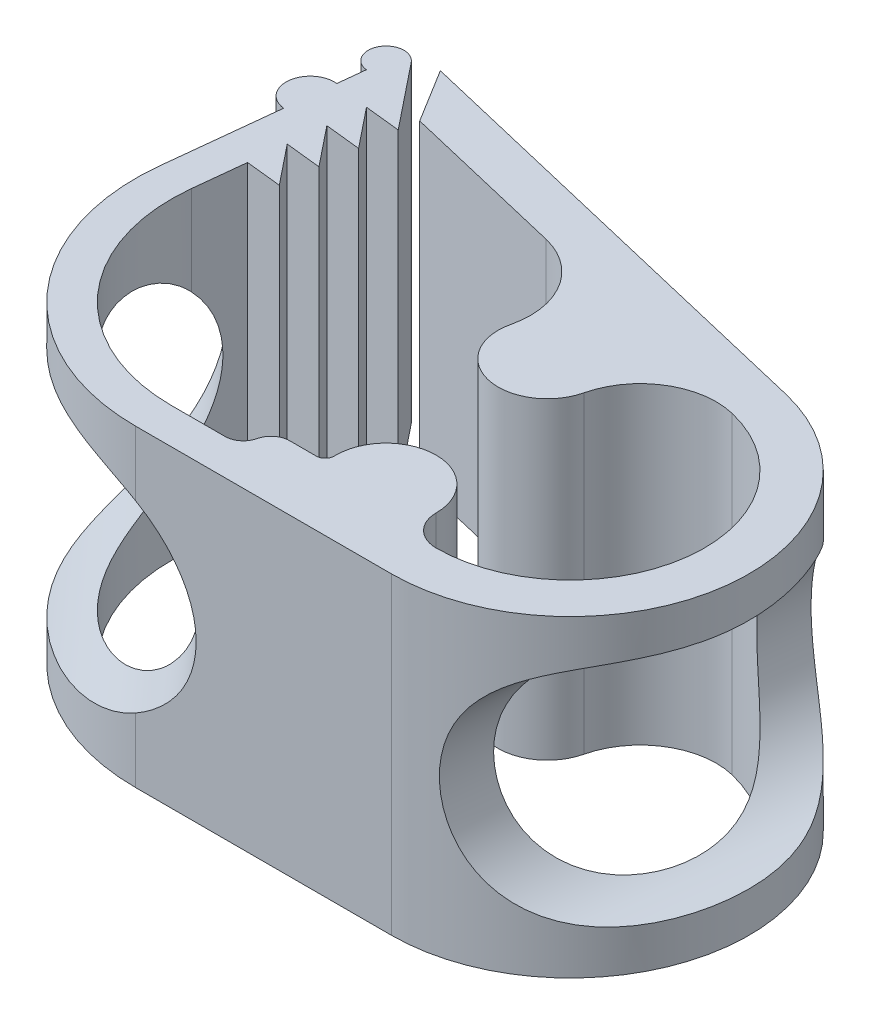
SolidWorks part; units mm, degrees
ref_plane "Front Plane" through (0, 0, 0) normal (0, 0, 1) x (1, 0, 0)
ref_plane "Top Plane" through (0, 0, 0) normal (0, 1, 0) x (1, 0, 0)
ref_plane "Right Plane" through (0, 0, 0) normal (1, 0, 0) x (0, 0, -1)
sketch "Sketch1" plane through (0, 0, 0) normal (0, 1, 0) x (1, 0, 0)
  line L0 (14.3, -12) -> (0, -12)
  line L1 (-11.9306, 1.2885) -> (-11.2565, 7.5301)
  line L2 (-10.9666, 10.2145) -> (-10.8056, 11.7058)
  line L3 (-9.9174, 13.3248) -> (-7.001, 9.6806)
  line L4 (-7.001, 9.6806) -> (-8.9895, 9.8954)
  line L5 (-8.9895, 9.8954) -> (-7.217, 7.6806)
  line L6 (-7.217, 7.6806) -> (-9.2055, 7.8954)
  line L7 (-9.2055, 7.8954) -> (-7.433, 5.6806)
  line L8 (-7.433, 5.6806) -> (-9.4215, 5.8954)
  line L13 (-9.4215, 5.8954) -> (-7.649, 3.6806)
  line L14 (-7.649, 3.6806) -> (-9.6375, 3.8954)
  line L15 (-9.6375, 3.8954) -> (-9.9422, 1.0737)
  line L16 (0, -10) -> (3, -10)
  line L17 (5, -8.4) -> (6.5, -8.4)
  line L18 (7, -7.9) -> (7, -7.8)
  line L19 (2.4072, 8.5266) -> (-6.8367, 10.7176)
  line L21 (-6.8367, 10.7176) -> (-8.6928, 13.7268)
  line L22 (-8.6928, 13.7268) -> (16.6063, 7.7304)
  line L23 (3, -10) -> (5, -8.4) construction
  line L24 (14.3, -2) -> (14.3, -12) construction
  line L25 (14.3, -2) -> (16.6063, 7.7304) construction
  line L26 (5.5624, 3.411) -> (10.9141, 2.1426) construction
  line L27 (-25.5754, -10.6267) -> (-9.9942, 15.87) construction
  line L28 (10.7621, -27.7443) -> (29.0086, 3.2849) construction
  line L29 (-11.5602, 13.2069) -> (22.9201, -7.069) construction
  line L30 (-8.4592, 11.5027) -> (-7.7647, 12.2222) construction
  arc A0 (0, -12) -> (-11.9306, 1.2885) centre (0, 0) cw
  arc A1 (-11.2565, 7.5301) -> (-10.9666, 10.2145) centre (-11.1116, 8.8723) cw
  arc A2 (-10.8056, 11.7058) -> (-9.9174, 13.3248) centre (-10.6982, 12.7) cw
  arc A3 (-9.9422, 1.0737) -> (0, -10) centre (0, 0) ccw
  arc A4 (3, -10) -> (4, -9.2) centre (3, -8.975) ccw
  arc A5 (4, -9.2) -> (5, -8.4) centre (5, -9.425) cw
  arc A6 (6.5, -8.4) -> (7, -7.9) centre (6.5, -7.9) ccw
  arc A7 (7, -7.8) -> (12.6, -7.8) centre (9.8, -7.8) cw
  arc A8 (12.6, -7.8) -> (14.3, -9.5) centre (14.3, -7.8) ccw
  arc A9 (14.3, -9.5) -> (16.0297, 5.2978) centre (14.3, -2) ccw
  arc A10 (16.0297, 5.2978) -> (10.9141, 2.1426) centre (15.0496, 1.1624) ccw
  arc A11 (10.9141, 2.1426) -> (5.5624, 3.411) centre (8.2383, 2.7768) cw
  arc A12 (5.5624, 3.411) -> (2.4072, 8.5266) centre (1.427, 4.3912) ccw
  arc A14 (16.6063, 7.7304) -> (14.3, -12) centre (14.3, -2) cw
  point P16 (0, 0)
  point P17 (0, 0)
  point P18 (0, 0)
  point P19 (-6.226, 9.6806)
  point P39 (0, 0)
  point P58 (-10.6982, 13.7)
  point P68 (9.8, -5)
  point P75 (7.604, 0.1009)
  dimension "D5" = 1
  dimension "D6" = 1.35
  dimension "D8" = 2.5
  dimension "D10" = 2.5
  dimension "D13" = 12
  dimension "D17" = 2.8
  dimension "D19" = 0.5
  dimension "D22" = 2.75
  dimension "D12" = 45
  dimension "D24" = 40
  dimension "D25" = 10
  dimension "D1" = 2
  dimension "D2" = 25.7
  dimension "D3" = 2
  dimension "D4" = 2
  dimension "D7" = 1.5
  dimension "D9" = 1
  dimension "D14" = 3
  dimension "D15" = 3.6
  dimension "D16" = 2
  dimension "D18" = 7
  dimension "D20" = 1.5
  dimension "D23" = 9.5
  dimension "D26" = 26
extrude "Boss-Extrude3" add sketch "Sketch1" along normal mid plane 17.5
ref_plane "Plane1" through (-0.0379, 0, 0.324) normal (-0.1161, 0, 0.9932) x (0.9932, 0, 0.1161)
sketch "Sketch2" plane through (-0.0379, 0, 0.324) normal (-0.1161, 0, 0.9932) x (0.9932, 0, 0.1161)
  line L0 (24.4355, -8.75) -> (24.4355, 8.75) construction
  circle A0 centre (24.4355, 0) radius 6.5
  dimension "D1" = 13
extrude "Cut-Extrude1" cut sketch "Sketch2" against normal through all both and the other way through all
ref_plane "Plane2" through (0, 0, 0) normal (-0.6681, 0, -0.7441) x (-0.7441, 0, 0.6681)
sketch "Sketch3" plane through (0, 0, 0) normal (-0.6681, 0, -0.7441) x (-0.7441, 0, 0.6681)
  line L0 (12, -8.75) -> (12, 8.75) construction
  circle A0 centre (12, 0) radius 6.5
  dimension "D1" = 13
extrude "Cut-Extrude2" cut sketch "Sketch3" against normal through all both and the other way through all
